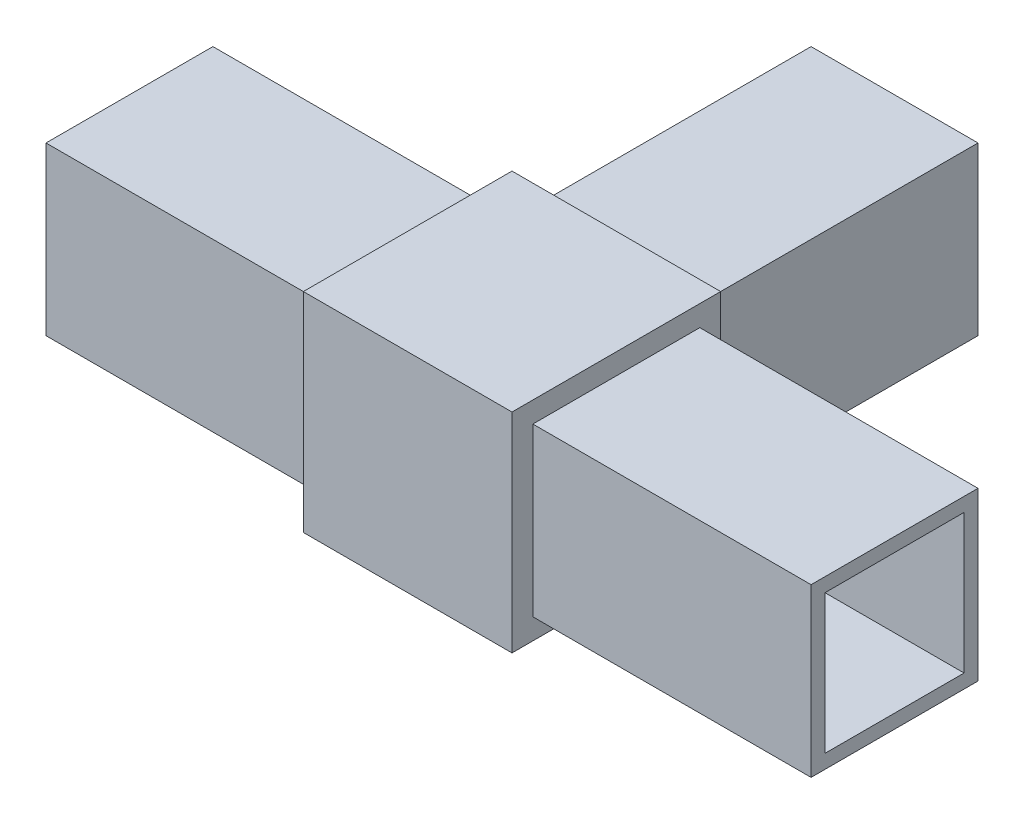
SolidWorks part; units mm, degrees
ref_plane "Alzado" through (0, 0, 0) normal (0, 0, 1) x (1, 0, 0)
ref_plane "Planta" through (0, 0, 0) normal (0, 1, 0) x (1, 0, 0)
ref_plane "Vista lateral" through (0, 0, 0) normal (1, 0, 0) x (0, 0, -1)
sketch "Croquis1" plane through (0, 0, 0) normal (0, 1, 0) x (1, 0, 0)
  line L1 (15, -15) -> (-15, -15)
  line L2 (15, -15) -> (15, 15)
  line L3 (15, 15) -> (-15, 15)
  line L4 (-15, -15) -> (-15, 15)
  line L5 (15, -15) -> (-15, 15) construction
  line L6 (15, 15) -> (-15, -15) construction
  line L7 (15, -15) -> (55, -15)
  line L8 (15, -15) -> (15, 15)
  line L9 (15, 15) -> (55, 15)
  line L10 (55, -15) -> (55, 15)
  line L11 (-15, 15) -> (15, 15)
  line L12 (-15, 15) -> (-15, 55)
  line L13 (-15, 55) -> (15, 55)
  line L14 (15, 15) -> (15, 55)
  line L15 (-15, -15) -> (-55, -15)
  line L16 (-15, -15) -> (-15, 15)
  line L17 (-15, 15) -> (-55, 15)
  line L18 (-55, -15) -> (-55, 15)
  point P0 (0, 0)
  dimension "D1" = 30
  dimension "D2" = 30
  dimension "D3" = 40
  dimension "D4" = 40
  dimension "D5" = 40
extrude "Extruir1" add sketch "Croquis1" along normal blind 30 contours L3 L14 L13 L12 | L4 L1 L2 L3 | L7 L10 L9 L2 | L18 L15 L4 L17
sketch "Croquis2" plane through (55, 0, 0) normal (1, 0, 0) x (0, 0, -1)
  line L4 (-15, 0) -> (15, 0)
  line L5 (15, 0) -> (15, 30)
  line L6 (15, 30) -> (-15, 30)
  line L7 (-15, 30) -> (-15, 0)
  line L8 (-15, 0) -> (15, 0)
  line L9 (15, 0) -> (15, 30)
  line L10 (15, 30) -> (-15, 30)
  line L11 (-15, 30) -> (-15, 0)
  line L16 (-12, 3) -> (12, 3)
  line L17 (12, 3) -> (12, 27)
  line L18 (12, 27) -> (-12, 27)
  line L19 (-12, 27) -> (-12, 3)
  line L20 (-12, 3) -> (12, 3)
  line L21 (12, 3) -> (12, 27)
  line L22 (12, 27) -> (-12, 27)
  line L23 (-12, 27) -> (-12, 3)
  dimension "D1" = 0
  dimension "D2" = 3
extrude "Extruir2" cut sketch "Croquis2" against normal blind 40
sketch "Croquis3" plane through (0, 0, -55) normal (0, 0, -1) x (-1, 0, 0)
  line L0 (-12, 3) -> (12, 3)
  line L1 (12, 3) -> (12, 27)
  line L2 (12, 27) -> (-12, 27)
  line L3 (-12, 27) -> (-12, 3)
  line L4 (-15, 0) -> (15, 0)
  line L5 (15, 0) -> (15, 30)
  line L6 (15, 30) -> (-15, 30)
  line L7 (-15, 30) -> (-15, 0)
  line L8 (-15, 0) -> (15, 0)
  line L9 (15, 0) -> (15, 30)
  line L10 (15, 30) -> (-15, 30)
  line L11 (-15, 30) -> (-15, 0)
  line L16 (15, 0) -> (15, 30) construction
  dimension "D1" = 0
  dimension "D2" = 3
extrude "Extruir3" cut sketch "Croquis3" against normal blind 40
sketch "Croquis5" plane through (-55, 0, 0) normal (-1, 0, 0) x (0, 0, 1)
  line L0 (-12, 3) -> (12, 3)
  line L1 (12, 3) -> (12, 27)
  line L2 (12, 27) -> (-12, 27)
  line L3 (-12, 27) -> (-12, 3)
  line L4 (-15, 0) -> (15, 0)
  line L5 (15, 0) -> (15, 30)
  line L6 (15, 30) -> (-15, 30)
  line L7 (-15, 30) -> (-15, 0)
  line L8 (-15, 0) -> (15, 0)
  line L9 (15, 0) -> (15, 30)
  line L10 (15, 30) -> (-15, 30)
  line L11 (-15, 30) -> (-15, 0)
  dimension "D1" = 0
  dimension "D2" = 3
extrude "Extruir4" cut sketch "Croquis5" against normal blind 40
shell "Vaciado1" thickness 2
